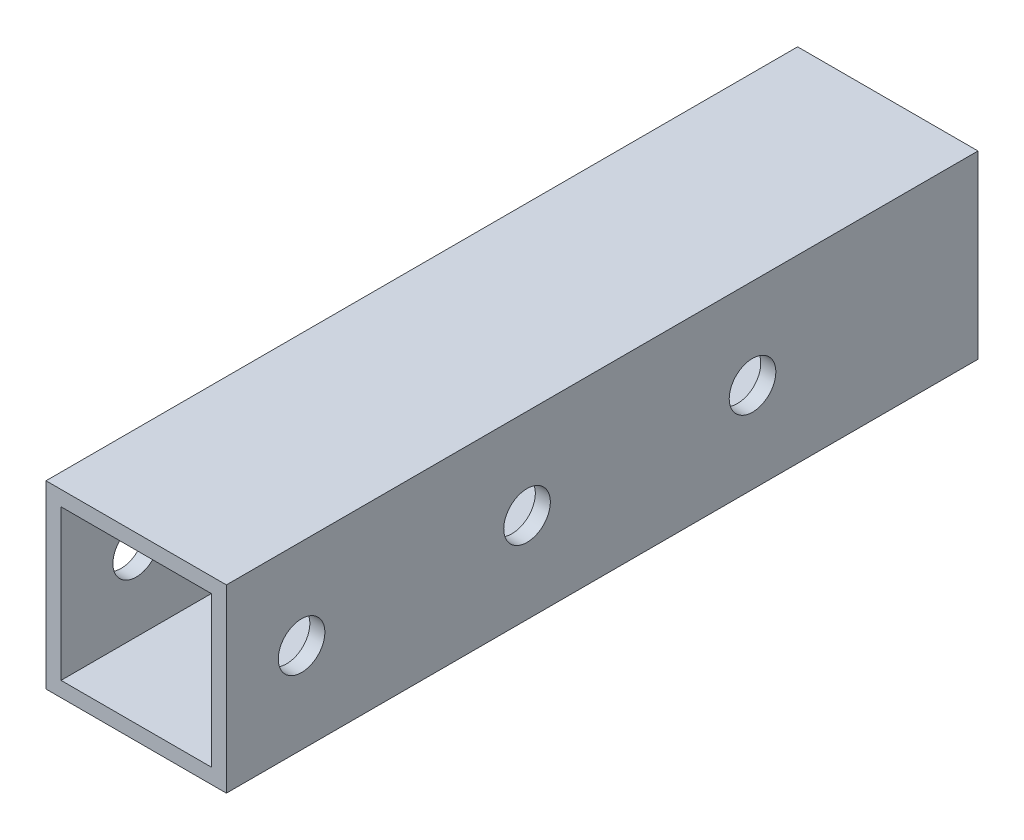
SolidWorks part; units mm, degrees
material "Thornel Mat VMA"
ref_plane "前视基准面" through (0, 0, 0) normal (0, 0, 1) x (1, 0, 0)
ref_plane "上视基准面" through (0, 0, 0) normal (0, 1, 0) x (1, 0, 0)
ref_plane "右视基准面" through (0, 0, 0) normal (1, 0, 0) x (0, 0, -1)
other "Configuration Table"
sketch "草图1" plane through (0, 0, 0) normal (0, 0, 1) x (1, 0, 0)
  line L0 (1, 1) -> (1, 11)
  line L1 (0, 0) -> (12, 0)
  line L2 (0, 0) -> (0, 12)
  line L3 (0, 12) -> (12, 12)
  line L4 (12, 0) -> (12, 12)
  line L5 (1, 11) -> (11, 11)
  line L6 (11, 1) -> (11, 11)
  line L7 (1, 1) -> (11, 1)
  dimension "D1" = 12
  dimension "D2" = 12
  dimension "D3" = 1
extrude "凸台-拉伸1" add sketch "草图1" along normal blind 50
sketch "草图2" [suppressed] plane through (0, 12, 0) normal (0, 1, 0) x (1, 0, 0)
  line L0 (6, 0) -> (6, -50) construction
  line L1 (12, 0) -> (0, 0) construction
  line L2 (12, -50) -> (0, -50) construction
  circle A0 centre (6, -15) radius 1.55
  circle A1 centre (6, -30) radius 1.55
  circle A2 centre (6, -45) radius 1.55
  dimension "D1" = 3.1
  dimension "D2" = 3.1
  dimension "D3" = 3.1
  dimension "D4" = 15
  dimension "D5" = 15
  dimension "D6" = 15
sketch "草图3" plane through (0, 0, 0) normal (-1, 0, 0) x (0, 0, 1)
  line L0 (0, 6) -> (50, 6) construction
  line L1 (0, 12) -> (0, 0) construction
  line L2 (50, 12) -> (50, 0) construction
  circle A0 centre (15, 6) radius 1.55
  circle A1 centre (30, 6) radius 1.55
  circle A2 centre (45, 6) radius 1.55
  dimension "D1" = 3.1
  dimension "D2" = 3.1
  dimension "D3" = 3.1
  dimension "D4" = 15
  dimension "D5" = 15
  dimension "D6" = 15
extrude "切除-拉伸1" cut sketch "草图3" against normal through all
